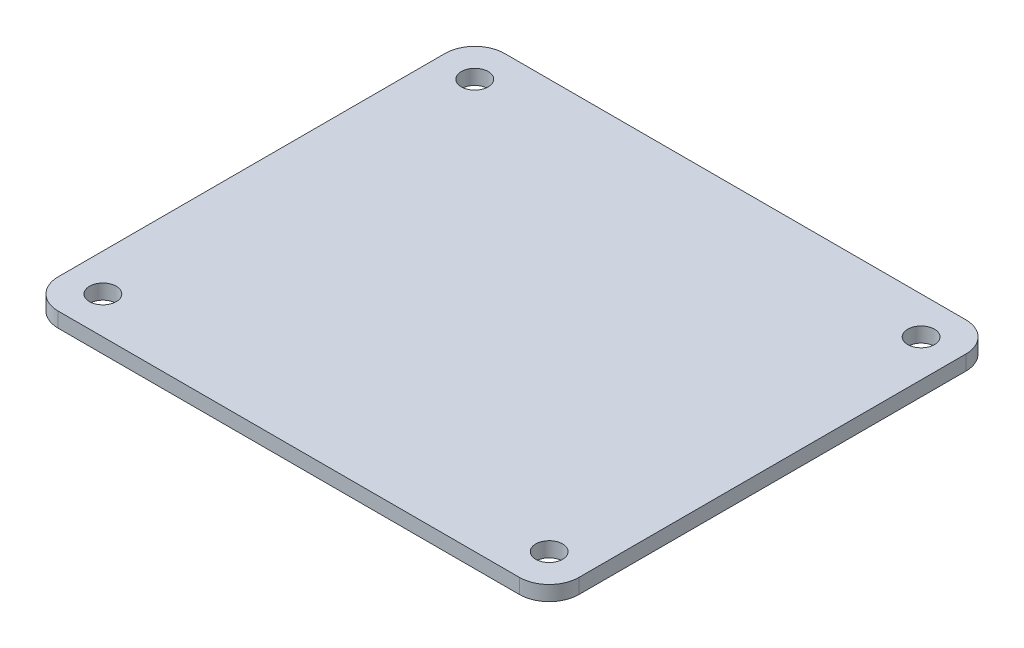
SolidWorks part; units mm, degrees
ref_plane "Front Plane" through (0, 0, 0) normal (0, 0, 1) x (1, 0, 0)
ref_plane "Top Plane" through (0, 0, 0) normal (0, 1, 0) x (1, 0, 0)
ref_plane "Right Plane" through (0, 0, 0) normal (1, 0, 0) x (0, 0, -1)
sketch "Sketch1" plane through (0, 0, 0) normal (0, 1, 0) x (1, 0, 0)
  line L1 (61.0821, -19.4532) -> (26.0821, -19.4532)
  line L2 (61.0821, -19.4532) -> (61.0821, 10.5468)
  line L3 (61.0821, 10.5468) -> (26.0821, 10.5468)
  line L4 (26.0821, -19.4532) -> (26.0821, 10.5468)
  dimension "D1" = 35
  dimension "D2" = 30
extrude "Boss-Extrude1" add sketch "Sketch1" along normal blind 1
fillet "Fillet1" radius 2 4 edges at (61.0821, 0.5, 19.4532) (26.0821, 0.5, 19.4532) (26.0821, 0.5, -10.5468) (61.0821, 0.5, -10.5468)
sketch "Sketch2" plane through (0, 1, 0) normal (0, 1, 0) x (1, 0, 0)
  line L0 (28.0821, -19.4532) -> (59.0821, -19.4532) construction
  line L1 (61.0821, -17.4532) -> (61.0821, 8.5468) construction
  line L2 (26.0821, 8.5468) -> (26.0821, -17.4532) construction
  line L3 (59.0821, 10.5468) -> (28.0821, 10.5468) construction
  circle A0 centre (58.5821, -16.9532) radius 0.9
  circle A1 centre (28.5821, -16.9532) radius 0.9
  circle A2 centre (28.5821, 8.0468) radius 0.9
  circle A3 centre (58.5821, 8.0468) radius 0.9
  dimension "D1" = 1.8
  dimension "D2" = 1.8
  dimension "D3" = 1.8
  dimension "D4" = 1.8
  dimension "D5" = 2.5
  dimension "D6" = 2.5
  dimension "D7" = 2.5
  dimension "D8" = 2.5
  dimension "D9" = 2.5
  dimension "D10" = 2.5
  dimension "D11" = 2.5
  dimension "D12" = 2.5
extrude "Cut-Extrude1" cut sketch "Sketch2" against normal blind 1
